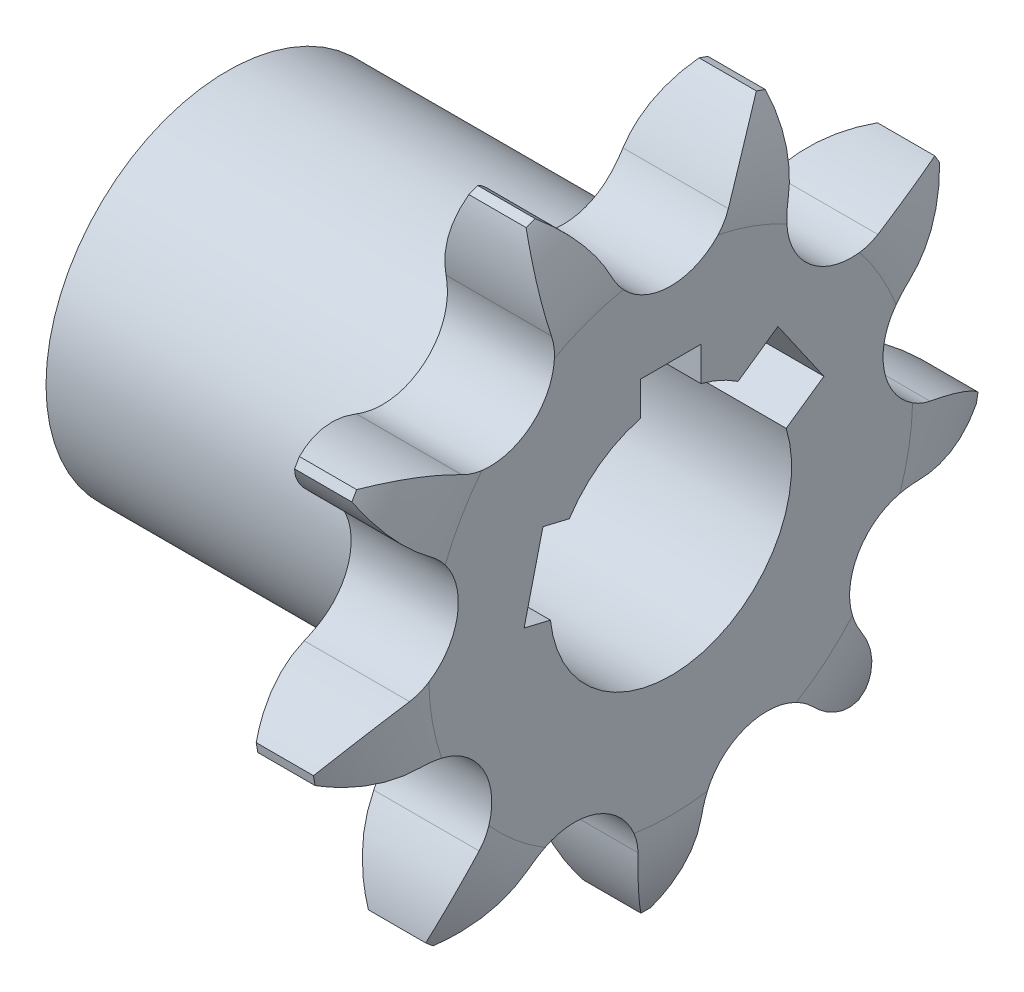
SolidWorks part; units mm, degrees
ref_plane "Plane1" through (0, 0, 0) normal (0, 0, 1) x (1, 0, 0)
ref_plane "Plane2" through (0, 0, 0) normal (0, 1, 0) x (1, 0, 0)
ref_plane "Plane3" through (0, 0, 0) normal (1, 0, 0) x (0, 0, -1)
sketch "Clipboard" plane through (0, 0, 0) normal (0, 1, 0) x (1, 0, 0)
  line L0 (0, 0) -> (9.4077, -1.49)
  line L1 (-15, 0) -> (100, 0) construction
  line L2 (0, 0) -> (-0.8203, 0.9272)
  line L3 (0, 0) -> (-8.8973, 3.4006)
  line L4 (0, 0) -> (3.0618, 0.4849)
  line L5 (0, 0) -> (-20.613, -7.688)
  line L6 (0, 0) -> (-4.4098, -2.9753)
  line L7 (-0.8203, 0.9272) -> (20.8459, 4.7475)
  line L8 (-76.2, 38.1) -> (-73.9, 38.1)
  line L9 (-73.3242, 40.7328) -> (-72.926, 40.7699)
  line L10 (-73.4529, 9.1872) -> (-63.2129, 9.1872)
  circle A0 centre (0, 0) radius 3.175
  circle A1 centre (0, 0) radius 8.4097
  circle A2 centre (0, 0) radius 9
  dimension "Dr" = 6.35
  dimension "MHD" = 16.8193
  dimension "Hub_dia" = 18
  dimension "Num_teeth" = 9
  dimension "Pitch" = 9.525
  dimension "Width" = 3.1
  dimension "Side_relief" = 1.238
  dimension "Side_radius" = 9.525
  dimension "Overall_len" = 22
  dimension "Show_teeth" = 9
  dimension "Thickness" = 5.3196
  dimension "OAL" = 22.0005
  dimension "T_dim" = 2.3
  dimension "Fillet_rad" = 0.4
  dimension "Face_width" = 5.32
  dimension "Num_strands" = 1
  dimension "Transv_pitch" = 10.24
  dimension "Plate_wid" = 8.26
sketch "BasProSke" plane through (0, 0, 0) normal (0, 1, 0) x (1, 0, 0)
  line L0 (-10, 0) -> (60, 0) construction
  line L1 (0, 0) -> (0, 12.0069)
  line L2 (0, 0) -> (5.3196, 0)
  line L3 (5.3196, 0) -> (5.3196, 12.0069)
  line L4 (4.0816, 16.7027) -> (1.238, 16.7027)
  arc A0 (0, 12.0069) -> (1.238, 16.7027) centre (9.525, 12.0069) cw
  arc A1 (5.3196, 12.0069) -> (4.0816, 16.7027) centre (-4.2054, 12.0069) ccw
  dimension "Thickness" = 5.3196
  dimension "D1" = 9.525
  dimension "G1" = 1.238
  dimension "G2" = 1.238
  dimension "Diameter" = 33.4055
revolve "Base-Revolve" add sketch "BasProSke" angle 360 about L0
sketch "TooCutSke" plane through (0, 0, 0) normal (1, 0, 0) x (0, 0, -1)
  line L0 (0, 13.9564) -> (2.9063, 12.6011) construction
  line L1 (0, 0) -> (0, 107) construction
  line L2 (0, 13.9564) -> (-10, 13.9564) construction
  line L3 (0, 13.9564) -> (-2.9063, 12.6011) construction
  arc A0 (2.9063, 12.6011) -> (5.9941, 16.1247) centre (10.503, 9.0588) cw
  arc A1 (2.9063, 12.6011) -> (-2.9063, 12.6011) centre (0, 13.9564) cw
  arc A2 (-2.9063, 12.6011) -> (-5.9941, 16.1247) centre (-10.503, 9.0588) ccw
  arc A3 (5.9941, 16.1247) -> (-5.9941, 16.1247) centre (0, 0) ccw
  dimension "R1" = 3.2067
  dimension "R2" = 8.382
  dimension "Overcut" = 17.2027
  dimension "Seat_radius" = 13.9564
  dimension "X" = 130
extrude "ToothCut" cut sketch "TooCutSke" along normal through all
pattern_circular "TeethCuts" count 9 every 40 about axis through (-10, 0, 0) along (1, 0, 0) of "ToothCut"
sketch "HubNeaOneSke" plane through (0, 0, 0) normal (-1, 0, 0) x (0, 0, 1)
  circle A0 centre (0, 0) radius 8.4097
  dimension "Diameter" = 16.8193
extrude "HubNearOne" add sketch "HubNeaOneSke" along normal blind 16.6809
fillet "HubNearOneFillet" radius 0.4 1 edges at (0, 0, -8.4097)
sketch "HubNeaBotSke" plane through (0, 0, 0) normal (-1, 0, 0) x (0, 0, 1)
  circle A0 centre (0, 0) radius 8.4097
  dimension "Diameter" = 16.8193
extrude "HubNearBoth" [suppressed] add sketch "HubNeaBotSke" along normal blind 8.3404
fillet "HubNearBothFillet" [suppressed] radius 0.4
ref_plane "FarPln" through (5.3196, 0, 0) normal (1, 0, 0) x (0, 0, -1)
sketch "HubFarSke" plane through (5.3196, 0, 0) normal (1, 0, 0) x (0, 0, -1)
  circle A0 centre (0, 0) radius 8.4097
  dimension "Diameter" = 16.8193
extrude "HubFar" [suppressed] add sketch "HubFarSke" along normal blind 8.3404
fillet "HubFarFillet" [suppressed] radius 0.4
sketch "BorSke" plane through (0, 0, 0) normal (1, 0, 0) x (0, 0, -1)
  circle A0 centre (0, 0) radius 6
  dimension "Diameter" = 12
extrude "Bore" cut sketch "BorSke" along normal mid plane 44.001
sketch "KeySke" plane through (0, 0, 0) normal (1, 0, 0) x (0, 0, -1)
  line L0 (-2.5, 0) -> (-2.5, 8.3)
  line L1 (-2.5, 8.3) -> (2.5, 8.3)
  line L2 (2.5, 8.3) -> (2.5, 0)
  line L3 (0, 0) -> (0, 34) construction
  line L4 (-2.5, 0) -> (2.5, 0)
  dimension "Offset" = 8.3
  dimension "Width" = 5
extrude "Keyway" [suppressed] cut sketch "KeySke" along normal mid plane 44.001
pattern_circular "Keyway2" [suppressed] count 2 every 90 about axis through (-10, 0, 0) along (1, 0, 0)
sketch "Sketch1" plane through (5.3196, 0, 0) normal (1, 0, 0) x (0, 0, -1)
  line L0 (-1.5, 7.5) -> (-1.5, 4.5)
  line L1 (-1.5, 7.5) -> (1.5, 7.5)
  line L2 (-1.5, 4.5) -> (1.5, 4.5)
  line L3 (1.5, 7.5) -> (1.5, 4.5)
  line L4 (-1.5, 7.5) -> (1.5, 4.5) construction
  line L5 (-1.5, 4.5) -> (1.5, 7.5) construction
  line L6 (0, 0) -> (0, 6) construction
  line L7 (-2, 7) -> (-2, 3) construction
  line L8 (-2, 7) -> (2, 7) construction
  line L9 (-2, 3) -> (2, 3) construction
  line L10 (2, 7) -> (2, 3) construction
  line L11 (-2, 7) -> (2, 3) construction
  line L12 (-2, 3) -> (2, 7) construction
  line L13 (-6.3383, 3.5813) -> (-2.4492, 2.646)
  line L14 (-6.3383, 3.5813) -> (-7.2736, -0.3078)
  line L15 (-2.4492, 2.646) -> (-3.3845, -1.2431)
  line L16 (-7.2736, -0.3078) -> (-3.3845, -1.2431)
  line L17 (-6.3383, 3.5813) -> (-3.3845, -1.2431) construction
  line L18 (-2.4492, 2.646) -> (-7.2736, -0.3078) construction
  line L19 (0, 0) -> (-4.8614, 1.1691) construction
  circle A0 centre (0, 0) radius 6 construction
  arc A1 (0, 5) -> (4.9927, -0.2701) centre (0, 0) cw construction
  point P1 (0, 6)
  point P13 (-4.8614, 1.1691)
  dimension "D2" = 5
  dimension "D1" = 3
  dimension "D3" = 4
extrude "Cut-Extrude1" cut sketch "Sketch1" against normal through all
sketch "Sketch2" plane through (-16.6809, 0, 0) normal (-1, 0, 0) x (0, 0, 1)
  line L0 (-5.3228, 6.3557) -> (-2.0372, 4.0742)
  line L1 (-5.3228, 6.3557) -> (-7.6043, 3.0702)
  line L2 (-2.0372, 4.0742) -> (-4.3188, 0.7886)
  line L3 (-7.6043, 3.0702) -> (-4.3188, 0.7886)
  line L4 (-5.3228, 6.3557) -> (-4.3188, 0.7886) construction
  line L5 (-2.0372, 4.0742) -> (-7.6043, 3.0702) construction
  line L6 (6.3383, 3.5813) -> (7.2736, -0.3078) construction
  arc A0 (-1.5, 5.8095) -> (5.9677, -0.6219) centre (0, 0) ccw construction
  point P1 (-4.8208, 3.5722)
extrude "Cut-Extrude2" cut sketch "Sketch2" against normal through all
sketch "Sketch3" plane through (-16.6809, 0, 0) normal (-1, 0, 0) x (0, 0, 1)
  circle A0 centre (0, 0) radius 9
  circle A1 centre (0, 0) radius 8.4097 construction
  circle A2 centre (0, 0) radius 8.4097
  dimension "D1" = 18
extrude "Boss-Extrude1" add sketch "Sketch3" against normal up to next
equation "' \"Pitch@Clipboard\" = 12.7"
equation "' \"Num_strands@Clipboard\" = 1"
equation "' \"Num_teeth@Clipboard\" = 9"
equation "' \"Hub_dia@Clipboard\" = 50"
equation "' \"Overall_len@Clipboard\" = 3"
equation "' \"Diameter@BorSke\" = 12"
equation "' \"T_dim@Clipboard\" = 1"
equation "' \"Width@KeySke\" = 2"
equation "' \"Dr@Clipboard\" = 8.51"
equation "' \"Face_width@Clipboard\" = 7.2"
equation "' \"Side_radius@Clipboard\" = 12.7"
equation "' \"Side_relief@Clipboard\" = 1.27"
equation "' \"Transv_pitch@Clipboard\" = 13.92"
equation "' \"Show_teeth@Clipboard\" = 9"
equation "' \"Fillet_rad@Clipboard\" = 0.6"
equation "' \"Plate_wid@Clipboard\" = 11.8"
equation "\"Num_teeth@Clipboard\" = int( \"Num_teeth@Clipboard\" )"
equation "\"Num_teeth@Clipboard\" = ((sgn( \"Num_teeth@Clipboard\" - 5.0)+1)*( \"Num_teeth@Clipboard\" - 5.0))/2 +5.0"
equation "\"Num_teeth@Clipboard\" = ((sgn( \"Num_teeth@Clipboard\" - 200.0)-1)*( \"Num_teeth@Clipboard\" - 200.0))/-2 +200.0"
equation "\"MHD@Clipboard\" = \"Pitch@Clipboard\" * (1.0 / tan(3.14159265 / \"Num_teeth@Clipboard\" )) - 1.04 * \"Plate_wid@Clipboard\" - 0.76"
equation "\"Thickness@Clipboard\"  = \"Face_width@Clipboard\" + (\"Num_strands@Clipboard\" - 1) * \"Transv_pitch@Clipboard\""
equation "\"OAL@Clipboard\" = \"Thickness@Clipboard\" + 2 * \"Fillet_rad@Clipboard\" + 1"
equation "\"MHD@Clipboard\" = ((sgn( \"MHD@Clipboard\" - \"Hub_dia@Clipboard\" )-1)*( \"MHD@Clipboard\" - \"Hub_dia@Clipboard\" ))/-2+ \"Hub_dia@Clipboard\""
equation "\"OAL@Clipboard\" = ((sgn( \"OAL@Clipboard\" - \"Overall_len@Clipboard\" )+1)*( \"OAL@Clipboard\" - \"Overall_len@Clipboard\" ))/2 + \"Overall_len@Clipboard\" + 0.0005"
equation "\"Num_teeth@TeethCuts\" = int( \"Show_teeth@Clipboard\" ) + 1"
equation "\"Num_teeth@TeethCuts\" = ((sgn( \"Num_teeth@TeethCuts\" - \"Num_teeth@Clipboard\" )-1)*( \"Num_teeth@TeethCuts\" - \"Num_teeth@Clipboard\" ))/-2+ \"Num_teeth@Clipboard\""
equation "\"Num_teeth@TeethCuts\" = ((sgn( \"Num_teeth@TeethCuts\" - 2.0)+1)*( \"Num_teeth@TeethCuts\" - 2.0))/2 +2.0"
equation "\"Angle@TeethCuts\" = 360.0 / \"Num_teeth@Clipboard\""
equation "\"Seat_radius@TooCutSke\" = ( \"Pitch@Clipboard\" / 2.0) / sin(3.14159265 / \"Num_teeth@Clipboard\" ) - \"Dr@Clipboard\" / 2.0 + \"Dr@Clipboard\" * 0.505"
equation "\"R1@TooCutSke\"  = \"Dr@Clipboard\" * 0.505"
equation "\"X@TooCutSke\" = 140.0 - (90.0 / \"Num_teeth@Clipboard\")"
equation "\"R2@TooCutSke\" = 0.12 * \"Dr@Clipboard\" * ( \"Num_teeth@Clipboard\" + 2.0)"
equation "\"Overcut@TooCutSke\" = 0.5 + 0.625 * \"Pitch@Clipboard\" - 0.5 * \"Dr@Clipboard\"  +  \"Pitch@Clipboard\" / 2.0 / sin(3.14159265 / \"Num_teeth@Clipboard\" )"
equation "\"Diameter@BasProSke\" = 2.0 * ( 0.625 * \"Pitch@Clipboard\" - 0.5 * \"Dr@Clipboard\"  +  \"Pitch@Clipboard\" / 2.0 / sin(3.14159265 / \"Num_teeth@Clipboard\" ))"
equation "\"Thickness@BasProSke\"  = \"Thickness@Clipboard\""
equation "\"G1@BasProSke\" =  \"Side_relief@Clipboard\""
equation "\"G2@BasProSke\" =  \"Side_relief@Clipboard\""
equation "\"D1@BasProSke\" =  \"Side_radius@Clipboard\""
equation "\"Diameter@HubNeaOneSke\" = \"MHD@Clipboard\""
equation "\"Length@HubNearOne\" = \"OAL@Clipboard\" - \"Thickness@BasProSke\""
equation "\"Diameter@HubNeaBotSke\" = \"MHD@Clipboard\""
equation "\"Length@HubNearBoth\" = ( \"OAL@Clipboard\" - \"Thickness@BasProSke\" ) / 2.0"
equation "\"D1@HubNearOneFillet\" = \"Fillet_rad@Clipboard\""
equation "\"D1@HubNearBothFillet\" = \"Fillet_rad@Clipboard\""
equation "\"Thickness@FarPln\" = \"Thickness@BasProSke\""
equation "\"Diameter@HubFarSke\" = \"MHD@Clipboard\""
equation "\"Length@HubFar\" = ( \"OAL@Clipboard\" - \"Thickness@BasProSke\" ) / 2.0"
equation "\"D1@HubFarFillet\" = \"Fillet_rad@Clipboard\""
equation "\"D1@Bore\" = \"OAL@Clipboard\" * 2.0"
equation "\"D1@Keyway\" = \"OAL@Clipboard\" * 2.0"
equation "\"Offset@KeySke\" = \"T_dim@Clipboard\" + \"Diameter@BorSke\" / 2.0"
